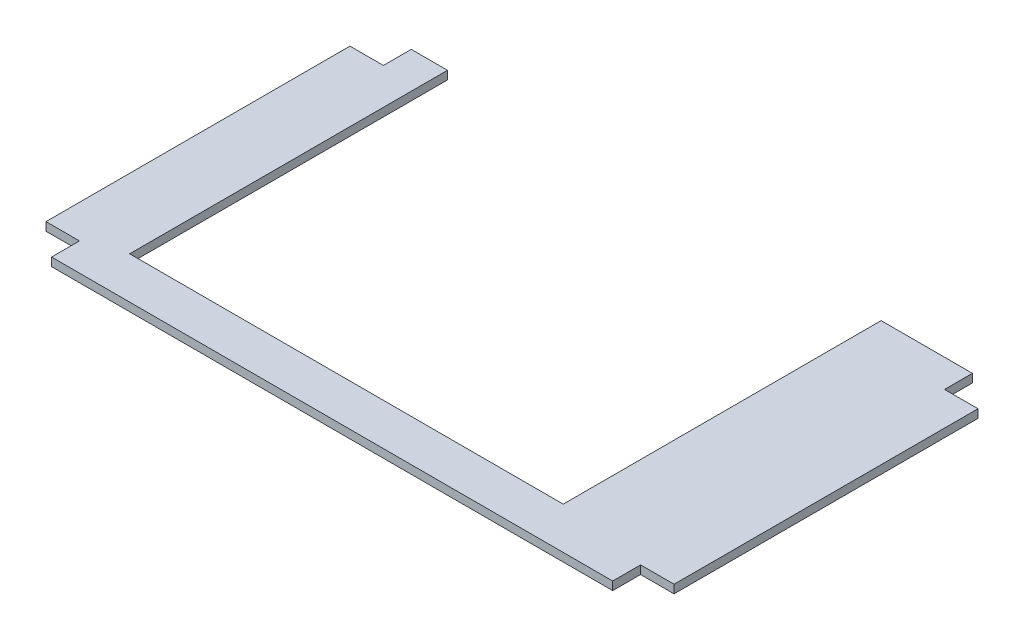
SolidWorks part; units mm, degrees
ref_plane "Front Plane" through (0, 0, 0) normal (0, 0, 1) x (1, 0, 0)
ref_plane "Top Plane" through (0, 0, 0) normal (0, 1, 0) x (1, 0, 0)
ref_plane "Right Plane" through (0, 0, 0) normal (1, 0, 0) x (0, 0, -1)
sketch "Sketch1" plane through (0, 0, 0) normal (0, 1, 0) x (1, 0, 0)
  line L0 (-112.62, 129) -> (-112.62, 0)
  line L1 (-112.62, 0) -> (112.62, 0)
  line L2 (112.62, 0) -> (112.62, 129)
  line L7 (112.62, 129) -> (-112.62, 129)
  dimension "D1" = 129
  dimension "D2" = 225.24
extrude "Boss-Extrude1" add sketch "Sketch1" along normal blind 3
sketch "Sketch2" plane through (0, 3, 0) normal (0, 1, 0) x (1, 0, 0)
  line L0 (112.62, 129) -> (-112.62, 129) construction
  line L1 (-112.62, 129) -> (-100.62, 129)
  line L2 (-112.62, 129) -> (-112.62, 119)
  line L3 (-112.62, 119) -> (-100.62, 119)
  line L4 (-100.62, 129) -> (-100.62, 119)
  line L5 (112.62, 129) -> (100.62, 129)
  line L6 (112.62, 129) -> (112.62, 119)
  line L7 (112.62, 119) -> (100.62, 119)
  line L8 (100.62, 129) -> (100.62, 119)
  line L9 (112.62, 0) -> (100.62, 0)
  line L10 (112.62, 0) -> (112.62, 10)
  line L11 (112.62, 10) -> (100.62, 10)
  line L12 (100.62, 0) -> (100.62, 10)
  line L13 (-112.62, 0) -> (-100.62, 0)
  line L14 (-112.62, 0) -> (-112.62, 10)
  line L15 (-112.62, 10) -> (-100.62, 10)
  line L16 (-100.62, 0) -> (-100.62, 10)
  line L17 (112.62, 0) -> (112.62, 129) construction
  line L24 (-112.62, 129) -> (-112.62, 0) construction
  line L25 (-87.62, 129) -> (67.88, 129)
  line L26 (-87.62, 129) -> (-87.62, 15)
  line L27 (-87.62, 15) -> (67.88, 15)
  line L28 (67.88, 129) -> (67.88, 15)
  dimension "D1" = 25
  dimension "D2" = 10
  dimension "D3" = 12
  dimension "D6" = 44.74
  dimension "D7" = 114
extrude "Cut-Extrude1" cut sketch "Sketch2" against normal through all
